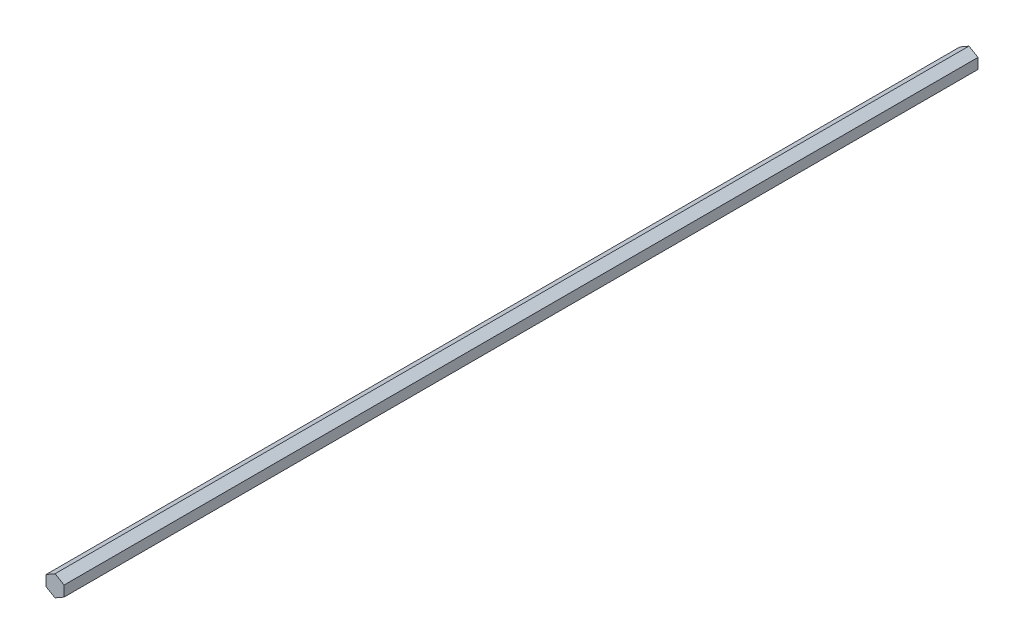
SolidWorks part; units mm, degrees
material "6061-T6 (SS)"
ref_plane "Front Plane" through (0, 0, 0) normal (0, 0, 1) x (1, 0, 0)
ref_plane "Top Plane" through (0, 0, 0) normal (0, 1, 0) x (1, 0, 0)
ref_plane "Right Plane" through (0, 0, 0) normal (1, 0, 0) x (0, 0, -1)
sketch "Sketch1" plane through (0, 0, 0) normal (0, 0, 1) x (1, 0, 0)
  line L1 (0, 7.3323) -> (-6.35, 3.6662)
  line L2 (-6.35, 3.6662) -> (-6.35, -3.6662)
  line L3 (-6.35, -3.6662) -> (0, -7.3323)
  line L4 (0, -7.3323) -> (6.35, -3.6662)
  line L5 (6.35, -3.6662) -> (6.35, 3.6662)
  line L6 (6.35, 3.6662) -> (0, 7.3323)
  circle A0 centre (0, 0) radius 6.35 construction
  point P1 (0, 0)
  dimension "D1" = 12.7
extrude "Boss-Extrude1" add sketch "Sketch1" along normal mid plane 640.3188
